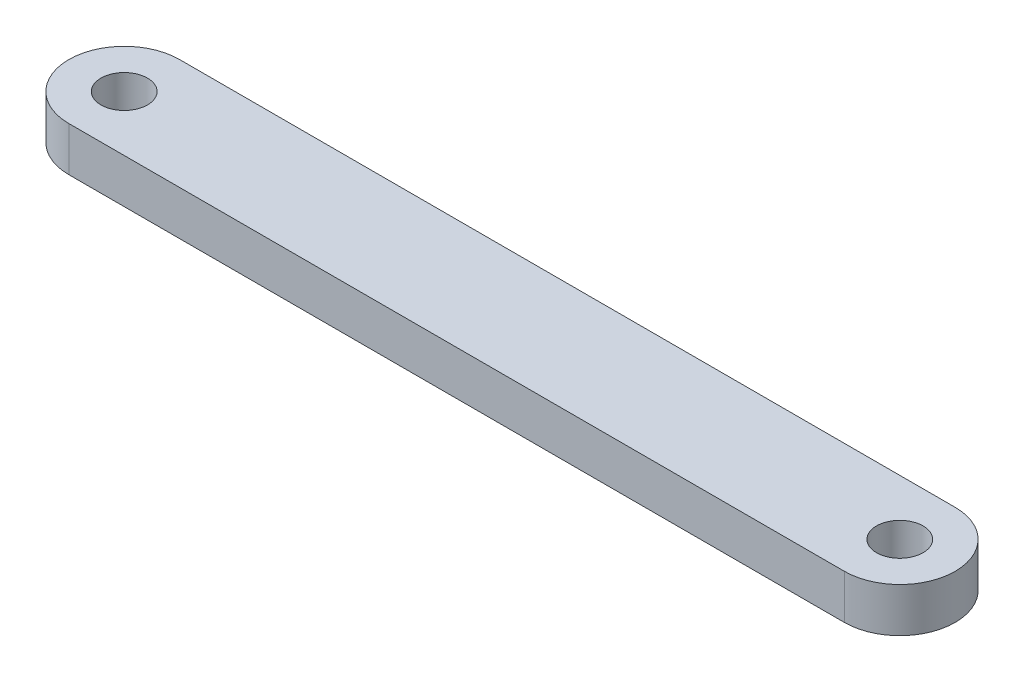
SolidWorks part; units mm, degrees
ref_plane "Front Plane" through (0, 0, 0) normal (0, 0, 1) x (1, 0, 0)
ref_plane "Top Plane" through (0, 0, 0) normal (0, 1, 0) x (1, 0, 0)
ref_plane "Right Plane" through (0, 0, 0) normal (1, 0, 0) x (0, 0, -1)
sketch "Sketch1" plane through (0, 0, 0) normal (0, 1, 0) x (1, 0, 0)
  line L0 (0, 0) -> (35, 0) construction
  line L1 (0, 2.5) -> (35, 2.5)
  line L2 (0, -2.5) -> (35, -2.5)
  arc A0 (0, 2.5) -> (0, -2.5) centre (0, 0) ccw
  arc A1 (35, -2.5) -> (35, 2.5) centre (35, 0) ccw
  circle A2 centre (0, 0) radius 1.05
  circle A3 centre (35, 0) radius 1.05
  point P3 (17.5, 0)
  dimension "D1" = 2.5
  dimension "D3" = 2.1
  dimension "D4" = 2.1
  dimension "D2" = 35
extrude "Boss-Extrude1" add sketch "Sketch1" along normal blind 2
